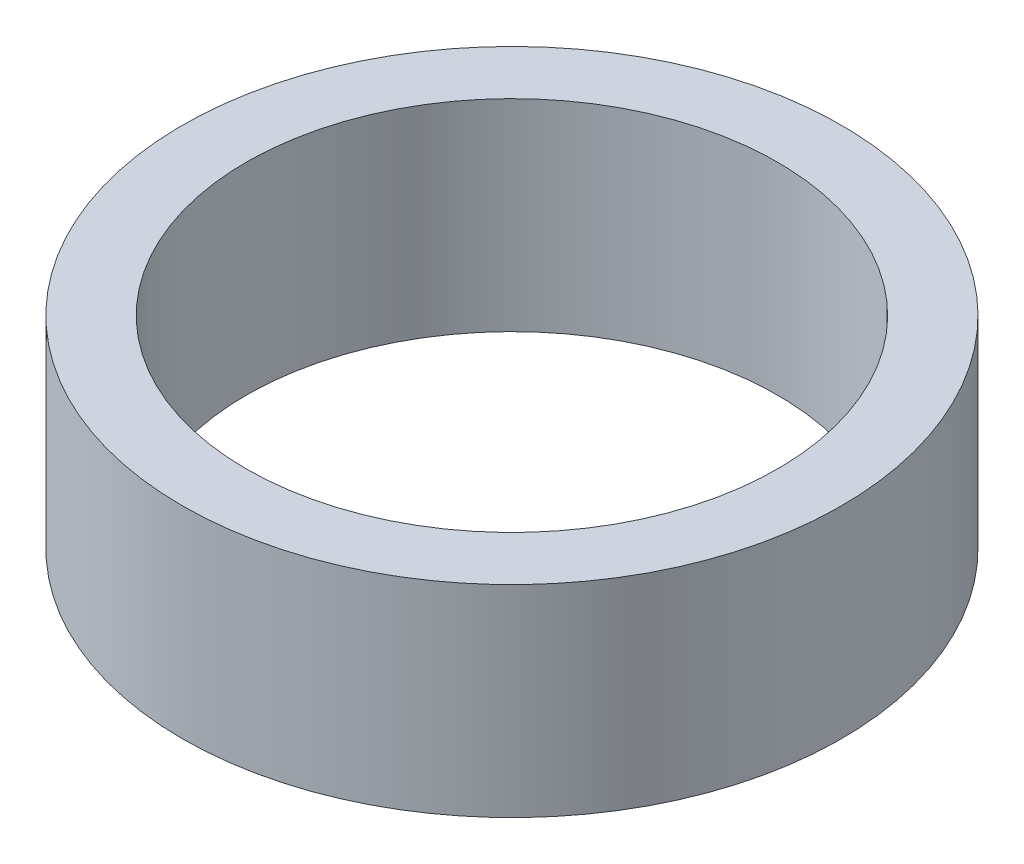
SolidWorks part; units mm, degrees
ref_plane "Front Plane" through (0, 0, 0) normal (0, 0, 1) x (1, 0, 0)
ref_plane "Top Plane" through (0, 0, 0) normal (0, 1, 0) x (1, 0, 0)
ref_plane "Right Plane" through (0, 0, 0) normal (1, 0, 0) x (0, 0, -1)
sketch "Sketch1" plane through (0, 0, 0) normal (0, 1, 0) x (1, 0, 0)
  circle A0 centre (0, 0) radius 4.9
  circle A2 centre (0, 0) radius 3.95
extrude "Boss-Extrude2" add sketch "Sketch1" along normal blind 3
